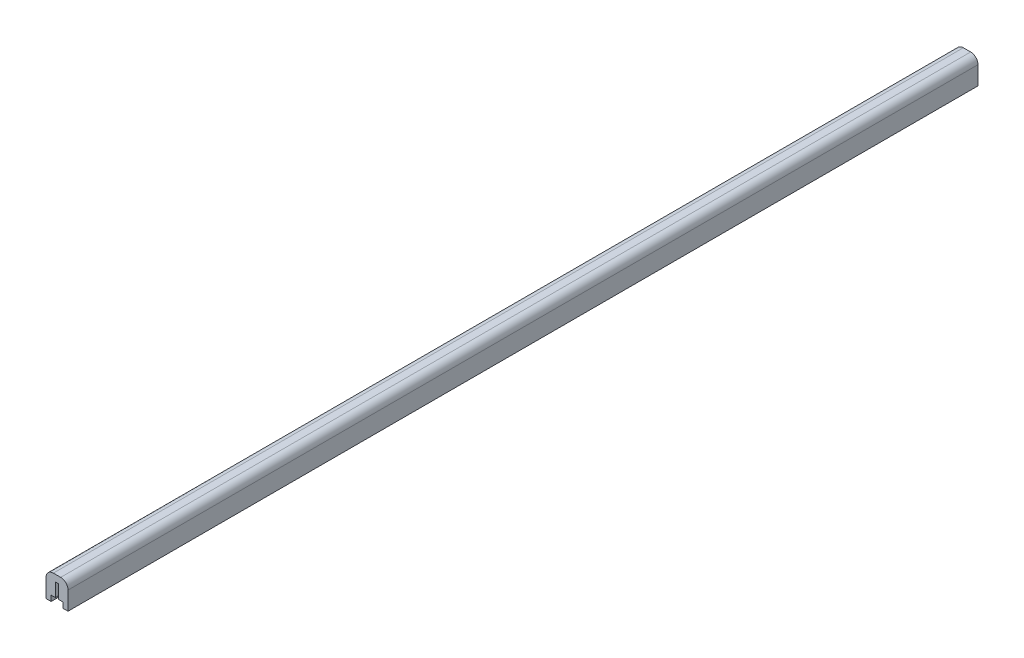
SolidWorks part; units mm, degrees
material "Pin"
ref_plane "Plan de face" through (0, 0, 0) normal (0, 0, 1) x (1, 0, 0)
ref_plane "Plan de dessus" through (0, 0, 0) normal (0, 1, 0) x (1, 0, 0)
ref_plane "Plan de droite" through (0, 0, 0) normal (1, 0, 0) x (0, 0, -1)
sketch "Esquisse1" plane through (0, 0, 0) normal (0, 0, 1) x (1, 0, 0)
  line L0 (-15, 0) -> (15, 0) construction
  line L1 (-15, 0) -> (-15, 25)
  line L2 (-5, 35) -> (5, 35)
  line L3 (15, 25) -> (15, 0)
  line L4 (-15, 0) -> (-8, 0)
  line L5 (-8, 0) -> (-8, 7.5)
  line L6 (-8, 7.5) -> (-2.25, 7.5)
  line L7 (-2.25, 7.5) -> (-2.25, 26)
  line L8 (-2.25, 26) -> (2.25, 26)
  line L9 (2.25, 26) -> (2.25, 7.5)
  line L10 (2.25, 7.5) -> (8, 7.5)
  line L11 (8, 7.5) -> (8, 0)
  line L12 (8, 0) -> (15, 0)
  line L13 (-8, 7.5) -> (8, 7.5) construction
  arc A0 (5, 35) -> (15, 25) centre (5, 25) cw
  arc A1 (-15, 25) -> (-5, 35) centre (-5, 25) cw
  point P3 (0, 0)
  point P15 (0, 26)
  point P19 (0, 7.5)
  dimension "D1" = 10
  dimension "D2" = 30
  dimension "D3" = 35
  dimension "D4" = 16
  dimension "D5" = 7.5
  dimension "D6" = 26
  dimension "D7" = 4.5
extrude "Boss.-Extru.1" add sketch "Esquisse1" along normal blind 1240
